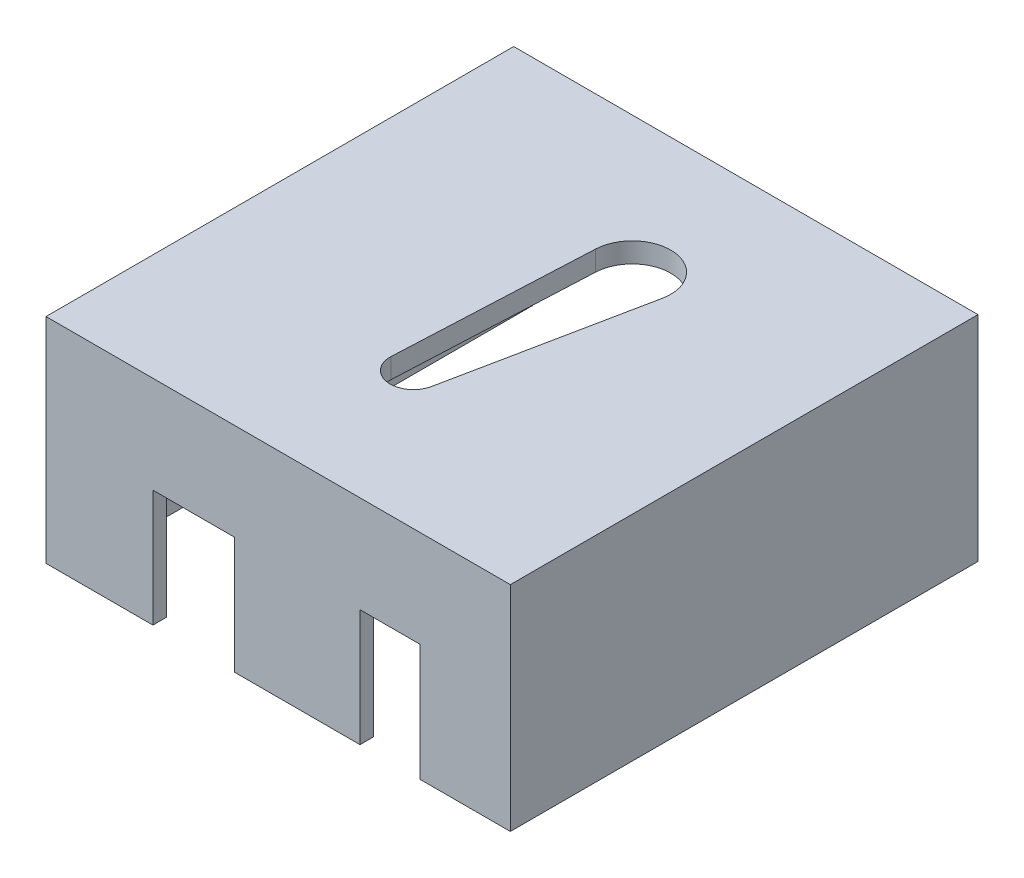
SolidWorks part; units mm, degrees
ref_plane "Front Plane" through (0, 0, 0) normal (0, 0, 1) x (1, 0, 0)
ref_plane "Top Plane" through (0, 0, 0) normal (0, 1, 0) x (1, 0, 0)
ref_plane "Right Plane" through (0, 0, 0) normal (1, 0, 0) x (0, 0, -1)
sketch "Sketch2" plane through (0, 0, 0) normal (0, 1, 0) x (1, 0, 0)
  line L1 (0, 0) -> (35.306, 0)
  line L2 (0, 0) -> (0, 71.12)
  line L3 (0, 71.12) -> (35.306, 71.12)
  line L4 (35.306, 0) -> (35.306, 71.12)
extrude "Boss-Extrude1" add sketch "Sketch2" along normal blind 3.048 contours L4 L3 L2 L1
sketch "Sketch6" plane through (0, 0, 0) normal (0, -1, 0) x (1, 0, 0)
  line L0 (35.306, 0) -> (35.306, -71.12) construction
  line L1 (0, 0) -> (35.306, 0)
  line L2 (0, 0) -> (0, -2.032)
  line L3 (0, -2.032) -> (35.306, -2.032)
  line L4 (35.306, 0) -> (35.306, -2.032)
extrude "Boss-Extrude3" add sketch "Sketch6" along normal blind 29.464 contours L3 L4 L1 L2
sketch "Sketch3" plane through (0, 0, 0) normal (0, -1, 0) x (1, 0, 0)
  line L1 (35.306, -71.12) -> (32.258, -71.12)
  line L2 (35.306, -71.12) -> (35.306, -2.032)
  line L3 (35.306, -2.032) -> (32.258, -2.032)
  line L4 (32.258, -71.12) -> (32.258, -2.032)
  line L5 (0, -2.032) -> (35.306, -2.032) construction
extrude "Boss-Extrude2" add sketch "Sketch3" along normal blind 29.464 contours L4 L3 L2 L1
sketch "Sketch4" plane through (0, 0, -71.12) normal (0, 0, -1) x (-1, 0, 0)
  line L0 (-32.258, -29.464) -> (-32.258, 0) construction
  line L1 (-33.274, -9.906) -> (-32.258, -9.906)
  line L2 (-33.274, -9.906) -> (-33.274, -11.811)
  line L3 (-33.274, -11.811) -> (-32.258, -11.811)
  line L4 (-32.258, -9.906) -> (-32.258, -11.811)
extrude "Cut-Extrude1" cut sketch "Sketch4" against normal up to surface (69.088 mm away) up to face at (16.129, -14.732, -2.032)
mirror "Mirror1" about plane through (0, 3.048, 0) normal (-1, 0, 0) of "Boss-Extrude3", "Boss-Extrude2", "Boss-Extrude1", "Cut-Extrude1"
sketch "Sketch7" plane through (0, 3.048, 0) normal (0, 1, 0) x (1, 0, 0)
  line L0 (3.2307, 20.1196) -> (9.1539, 49.2551)
  line L1 (-3.8061, 20.9954) -> (-2.4065, 50.694)
  arc A2 (-3.8061, 20.9954) -> (3.2307, 20.1196) centre (-0.254, 20.828) ccw
  arc A3 (-2.4065, 50.694) -> (9.1539, 49.2551) centre (3.429, 50.419) cw
extrude "Cut-Extrude2" cut sketch "Sketch7" against normal through all
sketch "Sketch8" plane through (0, 0, 0) normal (0, 0, 1) x (1, 0, 0)
  line L0 (-35.306, -29.464) -> (35.306, -29.464) construction
  line L1 (-6.604, -29.464) -> (-19.05, -29.464)
  line L2 (-6.604, -29.464) -> (-6.604, -11.684)
  line L3 (-6.604, -11.684) -> (-19.05, -11.684)
  line L4 (-19.05, -29.464) -> (-19.05, -11.684)
  line L6 (21.59, -29.464) -> (12.446, -29.464)
  line L7 (21.59, -29.464) -> (21.59, -11.684)
  line L8 (21.59, -11.684) -> (12.446, -11.684)
  line L9 (12.446, -29.464) -> (12.446, -11.684)
  point P10 (0, 0)
  point P11 (0, 0)
  point P12 (0, 0)
  point P13 (0, 0)
  point P14 (0, 0)
  point P15 (0, 0)
  point P16 (0, 0)
extrude "Cut-Extrude3" cut sketch "Sketch8" against normal through all contours L2 L3 L4 L1
